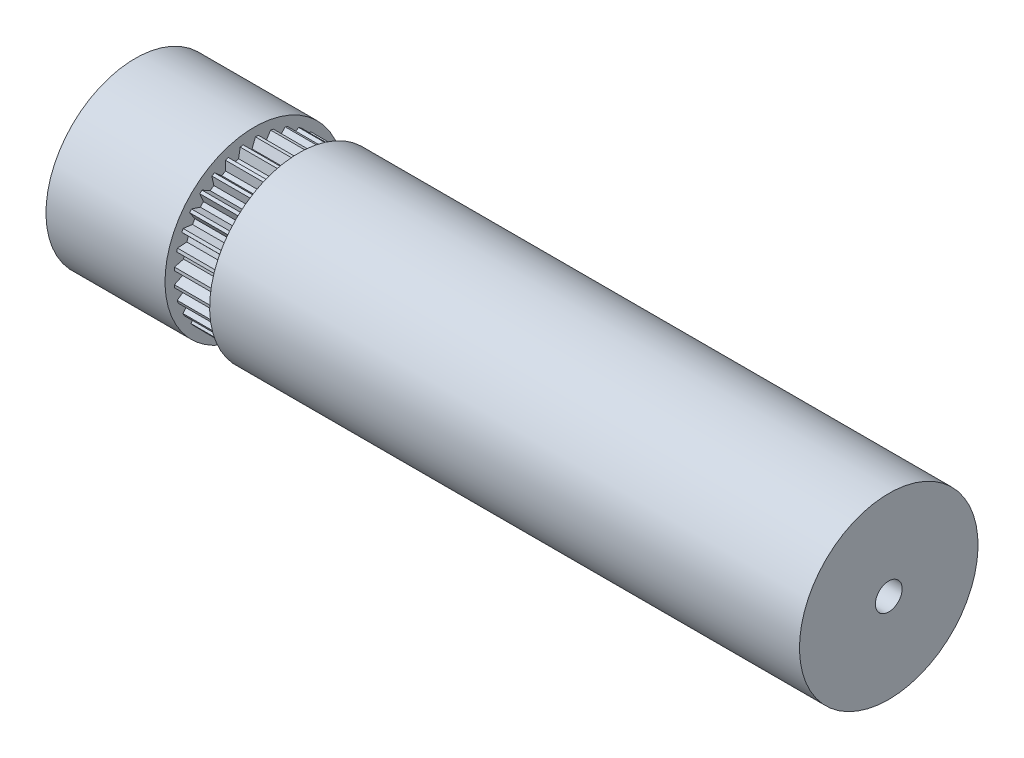
SolidWorks part; units mm, degrees
ref_plane "Plan de face" through (0, 0, 0) normal (0, 0, 1) x (1, 0, 0)
ref_plane "Plan de dessus" through (0, 0, 0) normal (0, 1, 0) x (1, 0, 0)
ref_plane "Plan de droite" through (0, 0, 0) normal (1, 0, 0) x (0, 0, -1)
sketch "Esquisse1" plane through (0, 0, 0) normal (0, 0, 1) x (1, 0, 0)
  line L0 (-81.1413, 0) -> (75.2437, 0) construction
  line L1 (-63.3, 15) -> (-63.3, 0)
  line L2 (63.3, 15) -> (63.3, 0)
  line L4 (-63.3, 15) -> (-43.3, 15)
  line L5 (-63.3, 0) -> (63.3, 0)
  line L6 (0, 15) -> (0, 0) construction
  line L10 (-35.8, 15) -> (63.3, 15)
  line L12 (-43.3, 15) -> (-43.3, 12)
  line L13 (-43.3, 12) -> (-35.8, 12)
  line L14 (-35.8, 15) -> (-35.8, 12)
  dimension "D1" = 63.3
  dimension "D4" = 15
  dimension "D6" = 7.5
  dimension "D7" = 3
revolve "Révolution1" add sketch "Esquisse1" angle 360 about L5
sketch "Esquisse3" plane through (-43.3, 0, 0) normal (1, 0, 0) x (0, 0, -1)
  line L0 (0, 0) -> (0.4912, 14.992) construction
  line L1 (-1.5159, 11.3463) -> (2.4996, 11.2147) construction
  line L2 (0.6911, 13.4545) -> (1.3692, 11.2518)
  line L3 (0.1911, 13.4709) -> (-0.6297, 11.3172)
  line L4 (-0.6297, 11.3172) -> (1.3692, 11.2518)
  line L5 (0.6911, 13.4545) -> (0.1911, 13.4709)
  circle A0 centre (0, 0) radius 15 construction
  point P12 (0.4649, 14.1893)
  dimension "D1" = 0.5
  dimension "D2" = 1
extrude "Boss.-Extru.1" add sketch "Esquisse3" along normal up to surface (7.5 mm away) up to face at (-35.8, -12, 0)
pattern_circular "Répétition circulaire1" count 33 over 360 about axis through (0, 0, 0) along (1, 0, 0) of "Boss.-Extru.1"
sketch "Esquisse7" plane through (-63.3, 0, 0) normal (-1, 0, 0) x (0, 0, 1)
  circle A0 centre (0, 0) radius 2.25
extrude "Enlèv. mat.-Extru.3" cut sketch "Esquisse7" along normal through all and the other way through all
